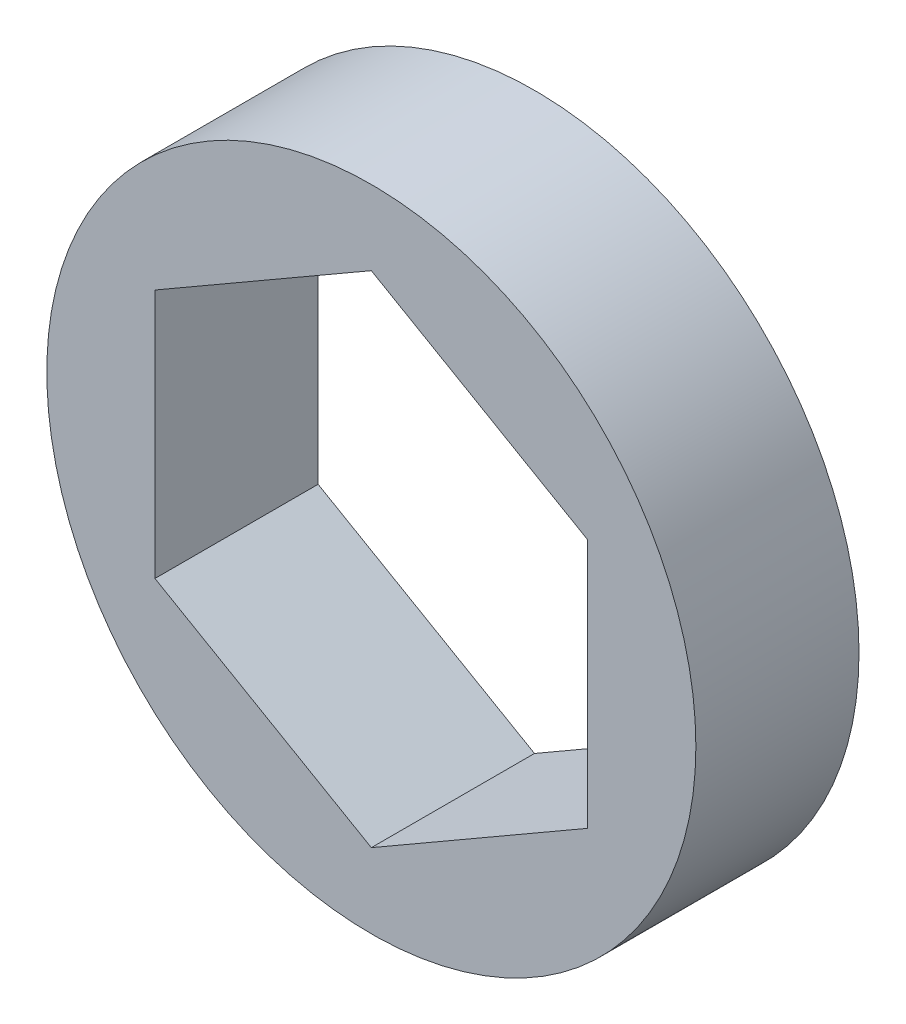
SolidWorks part; units mm, degrees
material "Nylon 101"
ref_plane "Front Plane" through (0, 0, 0) normal (0, 0, 1) x (1, 0, 0)
ref_plane "Top Plane" through (0, 0, 0) normal (0, 1, 0) x (1, 0, 0)
ref_plane "Right Plane" through (0, 0, 0) normal (1, 0, 0) x (0, 0, -1)
sketch "Sketch1" plane through (0, 0, 0) normal (0, 0, 1) x (1, 0, 0)
  line L1 (0, 7.3323) -> (-6.35, 3.6662)
  line L2 (-6.35, 3.6662) -> (-6.35, -3.6662)
  line L3 (-6.35, -3.6662) -> (0, -7.3323)
  line L4 (0, -7.3323) -> (6.35, -3.6662)
  line L5 (6.35, -3.6662) -> (6.35, 3.6662)
  line L6 (6.35, 3.6662) -> (0, 7.3323)
  circle A0 centre (0, 0) radius 9.525
  circle A1 centre (0, 0) radius 6.35 construction
  dimension "D1" = 12.7
  dimension "D2" = 19.05
extrude "Boss-Extrude1" add sketch "Sketch1" along normal blind 4.7879
